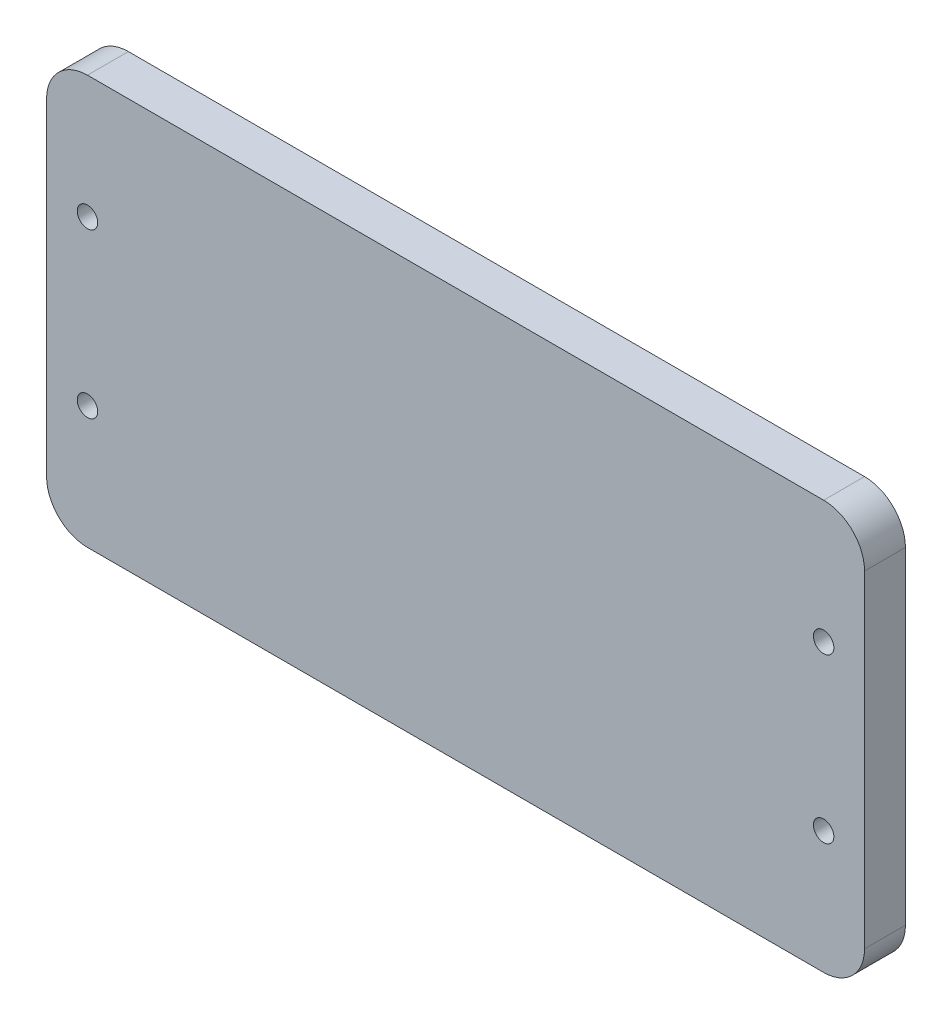
SolidWorks part; units mm, degrees
ref_plane "Front Plane" through (0, 0, 0) normal (0, 0, 1) x (1, 0, 0)
ref_plane "Top Plane" through (0, 0, 0) normal (0, 1, 0) x (1, 0, 0)
ref_plane "Right Plane" through (0, 0, 0) normal (1, 0, 0) x (0, 0, -1)
sketch "Sketch1" plane through (0, 0, 0) normal (0, 0, 1) x (1, 0, 0)
  line L0 (0, 42.602) -> (0, -32.2309) construction
  line L1 (-100, 50) -> (100, 50)
  line L2 (-100, 50) -> (-100, -50)
  line L3 (-100, -50) -> (100, -50)
  line L4 (100, 50) -> (100, -50)
  line L5 (-100, 50) -> (100, -50) construction
  line L6 (-100, -50) -> (100, 50) construction
  line L7 (-39.381, 0) -> (39.3035, 0) construction
  circle A0 centre (90, 20) radius 2.5
  circle A1 centre (-90, 20) radius 2.5
  circle A2 centre (90, -20) radius 2.5
  circle A3 centre (-90, -20) radius 2.5
  point P0 (0, 0)
  dimension "D3" = 5
  dimension "D4" = 30
  dimension "D5" = 10
  dimension "D1" = 200
  dimension "D2" = 100
extrude "Boss-Extrude1" add sketch "Sketch1" along normal blind 10
fillet "Fillet1" radius 10 4 edges at (-100, -50, 5) (-100, 50, 5) (100, -50, 5) (100, 50, 5)
